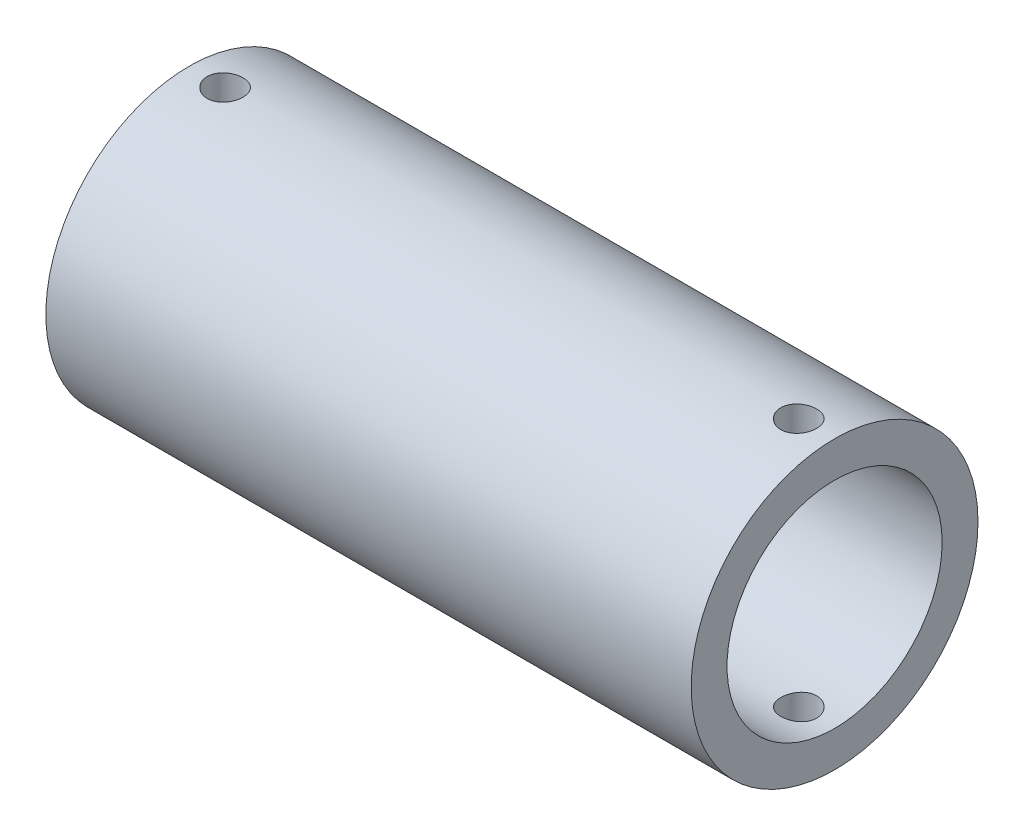
SolidWorks part; units mm, degrees
ref_plane "Alzado" through (0, 0, 0) normal (0, 0, 1) x (1, 0, 0)
ref_plane "Planta" through (0, 0, 0) normal (0, 1, 0) x (1, 0, 0)
ref_plane "Vista lateral" through (0, 0, 0) normal (1, 0, 0) x (0, 0, -1)
sketch "Croquis1" plane through (0, 0, 0) normal (1, 0, 0) x (0, 0, -1)
  circle A0 centre (0, 0) radius 40
  circle A1 centre (0, 0) radius 30
  dimension "D1" = 80
  dimension "D2" = 60
extrude "Saliente-Extruir1" add sketch "Croquis1" along normal mid plane 180
sketch "Croquis2" plane through (0, 0, 0) normal (0, 1, 0) x (1, 0, 0)
  line L0 (0, -57.4524) -> (0, 59.1876) construction
  circle A0 centre (-80, 0) radius 5
  circle A1 centre (80, 0) radius 5
  dimension "D1" = 80
  dimension "D2" = 10
extrude "Cortar-Extruir1" cut sketch "Croquis2" against normal through all both and the other way through all
